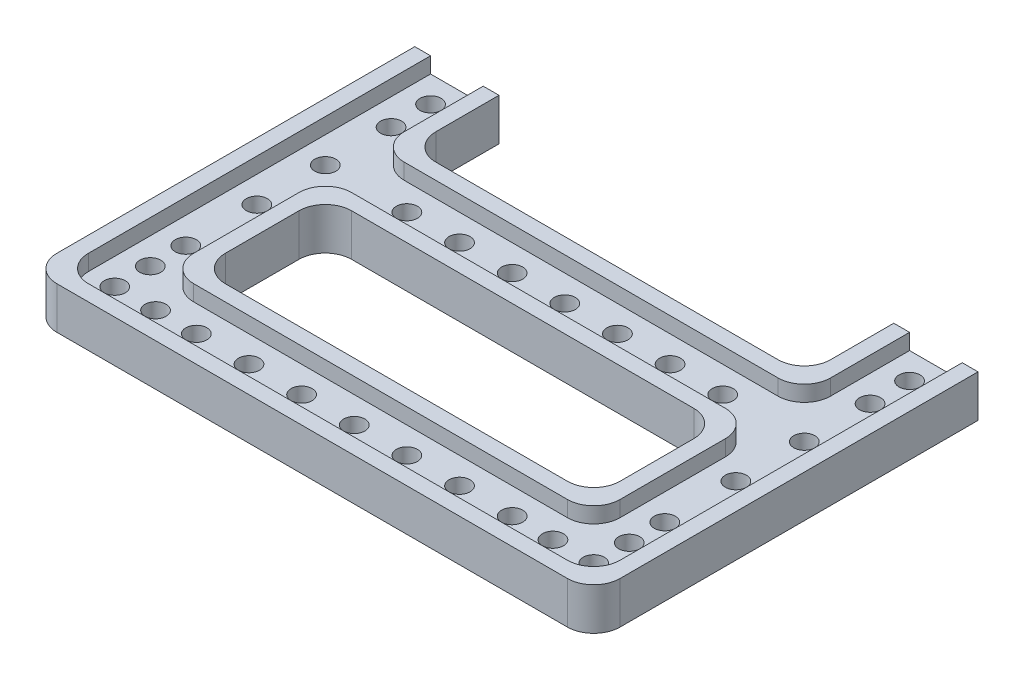
SolidWorks part; units mm, degrees
ref_plane "Front Plane" through (0, 0, 0) normal (0, 0, 1) x (1, 0, 0)
ref_plane "Top Plane" through (0, 0, 0) normal (0, 1, 0) x (1, 0, 0)
ref_plane "Right Plane" through (0, 0, 0) normal (1, 0, 0) x (0, 0, -1)
sketch "Sketch1" plane through (0, 0, 0) normal (0, 1, 0) x (1, 0, 0)
  line L1 (8, -48) -> (83, -48)
  line L2 (-8, 25) -> (-8, -48)
  line L6 (83, 25) -> (99, 25)
  line L8 (83, -48) -> (99, -48)
  line L9 (99, 25) -> (99, -48)
  line L10 (-8, 25) -> (8, 25)
  line L11 (-8, -48) -> (8, -48)
  line L14 (83, -32) -> (8, -32)
  line L16 (8, 25) -> (8, 8)
  line L17 (8, -8) -> (8, -32)
  line L18 (83, 8) -> (8, 8)
  line L19 (83, -32) -> (83, -8)
  line L20 (8, -8) -> (83, -8)
  line L21 (83, 8) -> (83, 25)
  circle A0 centre (0, 0) radius 2
  circle A1 centre (91, 0) radius 2
  circle A2 centre (0, -13) radius 2
  circle A3 centre (91, -13) radius 2
extrude "Boss-Extrude1" add sketch "Sketch1" along normal blind 5
sketch "Sketch2" plane through (0, 5, 0) normal (0, 1, 0) x (1, 0, 0)
  line L0 (-8, 25) -> (-8, -48)
  line L2 (-8, -48) -> (99, -48) construction
  line L5 (8, 25) -> (-8, 25) construction
  line L6 (-5, 25) -> (-8, 25)
  line L7 (99, 25) -> (99, -48)
  line L8 (99, -48) -> (96, -48)
  line L10 (99, 25) -> (83, 25) construction
  line L11 (96, 25) -> (99, 25)
  line L12 (8, 25) -> (5, 25)
  line L13 (5, 25) -> (5, 8)
  line L14 (5, 5) -> (86, 5)
  line L15 (5, 8) -> (5, 5)
  line L16 (8, 25) -> (8, 8)
  line L19 (86, 5) -> (86, 25)
  line L20 (86, 25) -> (83, 25)
  line L21 (83, 25) -> (83, 8)
  line L22 (8, 8) -> (83, 8)
  line L23 (86, -5) -> (86, -32)
  line L24 (83, -5) -> (86, -5)
  line L27 (86, -32) -> (86, -35)
  line L28 (86, -35) -> (5, -35)
  line L29 (5, -35) -> (5, -5)
  line L30 (5, -5) -> (83, -5)
  line L31 (-5, 25) -> (-5, -45)
  line L32 (-5, -45) -> (96, -45)
  line L34 (-8, -48) -> (96, -48)
  line L35 (96, 25) -> (96, -45)
  line L36 (8, -8) -> (83, -8)
  line L37 (83, -8) -> (83, -32)
  line L38 (83, -32) -> (8, -32)
  line L39 (8, -32) -> (8, -8)
extrude "Boss-Extrude3" add sketch "Sketch2" along normal blind 3
sketch "Sketch3" plane through (0, 5, 0) normal (0, 1, 0) x (1, 0, 0)
  circle A0 centre (0, -40) radius 2
  circle A1 centre (91, -40) radius 2
  circle A2 centre (91, -26.5) radius 2
  circle A3 centre (0, -26.5) radius 2
  circle A6 centre (0, 12.5) radius 2
  circle A7 centre (91, 12.5) radius 2
  circle A8 centre (0, 20) radius 2
  circle A9 centre (91, 20) radius 2
  circle A11 centre (0, -33.25) radius 2
  circle A12 centre (91, -33.25) radius 2
  circle A14 centre (75.5, 0) radius 2
  circle A15 centre (65.5, 0) radius 2
  circle A16 centre (55.5, 0) radius 2
  circle A17 centre (45.5, 0) radius 2
  circle A18 centre (35.5, 0) radius 2
  circle A19 centre (25.5, 0) radius 2
  circle A20 centre (15.5, 0) radius 2
  circle A21 centre (55.5, -40) radius 2
  circle A22 centre (45.5, -40) radius 2
  circle A23 centre (15.5, -40) radius 2
  circle A24 centre (75.5, -40) radius 2
  circle A25 centre (65.5, -40) radius 2
  circle A26 centre (25.5, -40) radius 2
  circle A27 centre (35.5, -40) radius 2
extrude "Cut-Extrude1" cut sketch "Sketch3" against normal up to surface (5 mm away) up to face at (0, 0, 15)
fillet "Fillet2" radius 5 16 edges at (5, 6.5, -5) (8, 4, -8) (83, 4, -8) (86, 6.5, -5) (86, 6.5, 5) (86, 6.5, 35) (5, 6.5, 35) (5, 6.5, 5) (96, 6.5, 45) (-5, 6.5, 45) (8, 4, 8) (8, 4, 32) (83, 4, 32) (83, 4, 8) (99, 4, 48) (-8, 4, 48)
sketch "Sketch4" plane through (0, 5, 0) normal (0, 1, 0) x (1, 0, 0)
  circle A0 centre (7.75, -40) radius 2
  circle A1 centre (83.25, -40) radius 2
extrude "Cut-Extrude2" cut sketch "Sketch4" against normal up to surface (5 mm away) up to face at (45.5, 0, 38)
sketch "Sketch5" plane through (0, 0, 0) normal (0, -1, 0) x (1, 0, 0)
  circle A0 centre (91, 0) radius 4
  circle A1 centre (91, 13) radius 4
  circle A2 centre (0, 0) radius 4
  circle A3 centre (0, 13) radius 4
extrude "Cut-Extrude3" cut sketch "Sketch5" against normal blind 2
